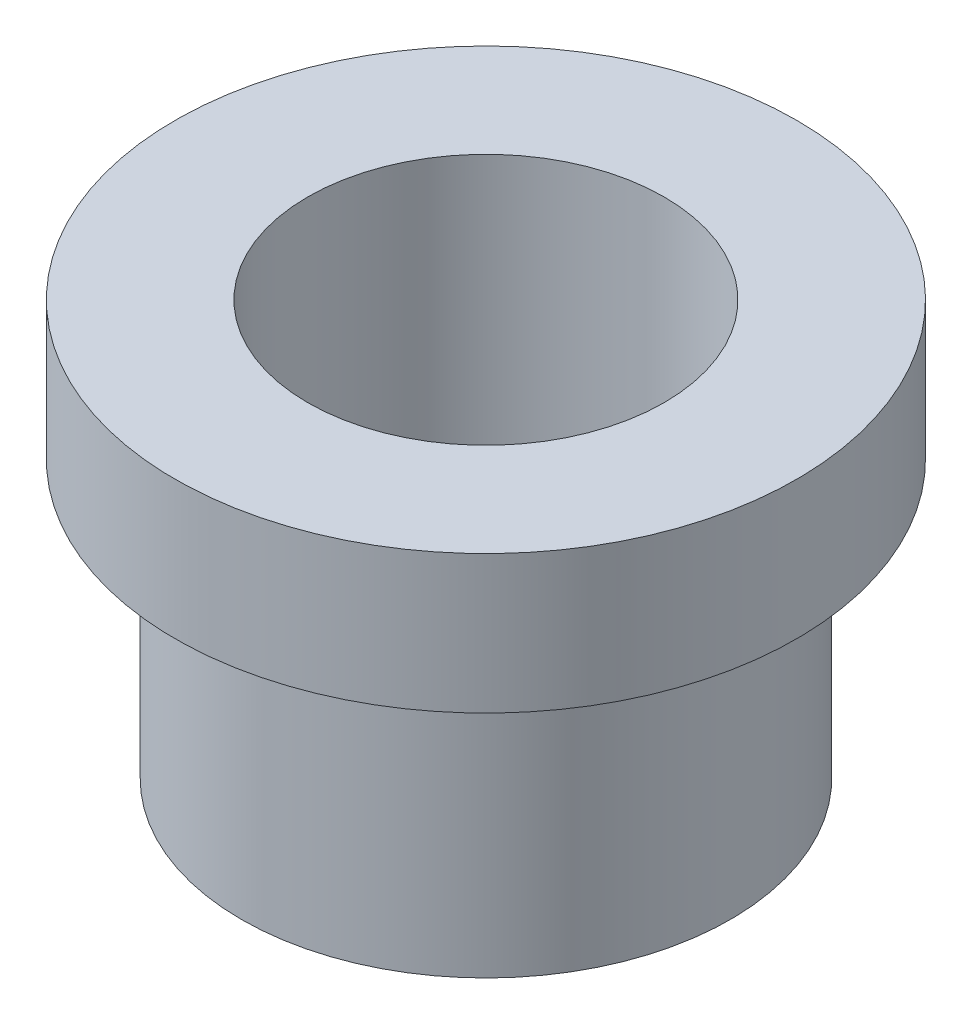
SolidWorks part; units mm, degrees
ref_plane "Front Plane" through (0, 0, 0) normal (0, 0, 1) x (1, 0, 0)
ref_plane "Top Plane" through (0, 0, 0) normal (0, 1, 0) x (1, 0, 0)
ref_plane "Right Plane" through (0, 0, 0) normal (1, 0, 0) x (0, 0, -1)
sketch "Sketch2" plane through (0, 0, 0) normal (0, 1, 0) x (1, 0, 0)
  circle A0 centre (0, 0) radius 16.383
  circle A1 centre (0, 0) radius 22.479
  circle A2 centre (0, 0) radius 19.431 construction
  circle A3 centre (0, 0) radius 28.575
  dimension "D1" = 32.766
  dimension "D2" = 44.958
  dimension "D3" = 38.862
  dimension "D4" = 57.15
extrude "Boss-Extrude1" add sketch "Sketch2" along normal blind 12.7 contours A2 | A0 | A3
sketch "Sketch3" plane through (0, 0, 0) normal (0, 1, 0) x (1, 0, 0)
  circle A1 centre (0, 0) radius 19.431
  circle A2 centre (0, 0) radius 19.431 construction
  circle A3 centre (0, 0) radius 22.479
  circle A4 centre (0, 0) radius 22.479
  circle A5 centre (0, 0) radius 16.383
  circle A6 centre (0, 0) radius 16.383
  dimension "D1" = 0
  dimension "D2" = 0
  dimension "D3" = 0
extrude "Boss-Extrude2" add sketch "Sketch3" against normal blind 25.4 contours A4 | A2
equation "\"D3@Sketch2\"=\"D1@Sketch2\"+(\"D2@Sketch2\"-\"D1@Sketch2\")/2"
